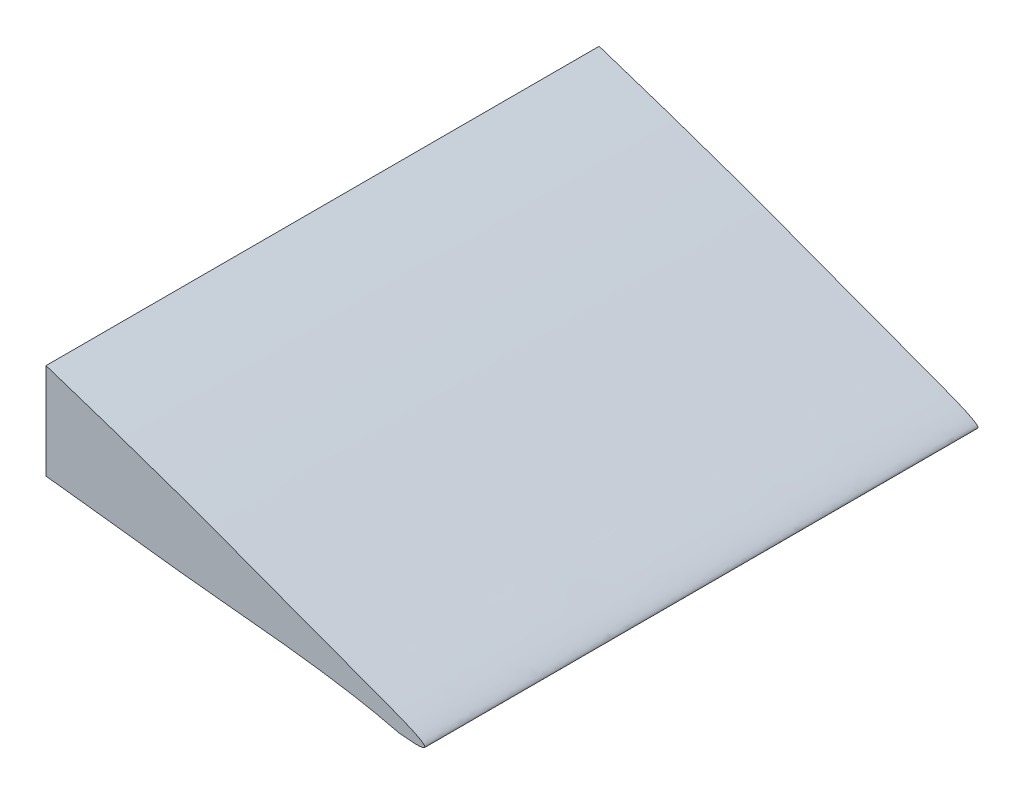
SolidWorks part; units mm, degrees
ref_plane "Front Plane" through (0, 0, 0) normal (0, 0, 1) x (1, 0, 0)
ref_plane "Top Plane" through (0, 0, 0) normal (0, 1, 0) x (1, 0, 0)
ref_plane "Right Plane" through (0, 0, 0) normal (1, 0, 0) x (0, 0, -1)
sketch "Sketch1" plane through (0, 0, 0) normal (0, 0, 1) x (1, 0, 0)
  spline S0 degree 3 poles (0.0006, 0.0001) (0.8106, 7.3592) (8.6491, 17.8566) (26.2867, 29.9752) (52.1111, 42.0692) (89.5976, 49.2908) (131.4008, 47.8848) (173.2567, 40.0411) (217.9611, 29.613) (256.9521, 19.5289) (290.3598, 8.711) (301.2732, 4.3828) (314.8169, -0.5162) (309.8463, 0.0001) knots 0 0 0 0 0.060864 0.113688 0.188609 0.312909 0.448482 0.557612 0.691544 0.852438 0.929756 0.976058 1 1 1 1
  spline S1 degree 3 poles (309.8463, 0.0001) (303.9568, 1.471) (293.9895, 2.094) (276.264, 4.5144) (260.8463, 5.4274) (235.8588, 7.8703) (205.1014, 8.8381) (157.7186, 9.0307) (110.4973, 6.1815) (66.5062, -0.5867) (36.4547, -6.0985) (15.3166, -6.1891) (1.2307, -6.9241) (0.0006, 0.0001) knots 0 0 0 0 0.057787 0.095275 0.171021 0.205339 0.335319 0.464904 0.658702 0.785512 0.893517 0.943092 1 1 1 1
extrude "Boss-Extrude1" add sketch "Sketch1" along normal blind 47.625
sketch "Sketch2" plane through (0, 0, 47.625) normal (0, 0, 1) x (1, 0, 0)
  circle A0 centre (20.32, 10.16) radius 6.35
  circle A1 centre (227.2963, 19.0501) radius 3.175
  dimension "D2" = 12.7
  dimension "D3" = 6.35
  dimension "D6" = 20.32
  dimension "D1" = 82.55
  dimension "D4" = 19.05
  dimension "D5" = 10.16
extrude "Cut-Extrude1" cut sketch "Sketch2" against normal through all
sketch "Sketch4" plane through (0, 0, 47.625) normal (0, 0, 1) x (1, 0, 0)
  line L1 (279.4006, -24.2166) -> (-31.7861, -24.2166)
  line L2 (279.4006, -24.2166) -> (279.4006, 93.2727)
  line L3 (279.4006, 93.2727) -> (-31.7861, 93.2727)
  line L4 (-31.7861, -24.2166) -> (-31.7861, 93.2727)
  dimension "D1" = 279.4
extrude "Cut-Extrude3" cut sketch "Sketch4" against normal through all
